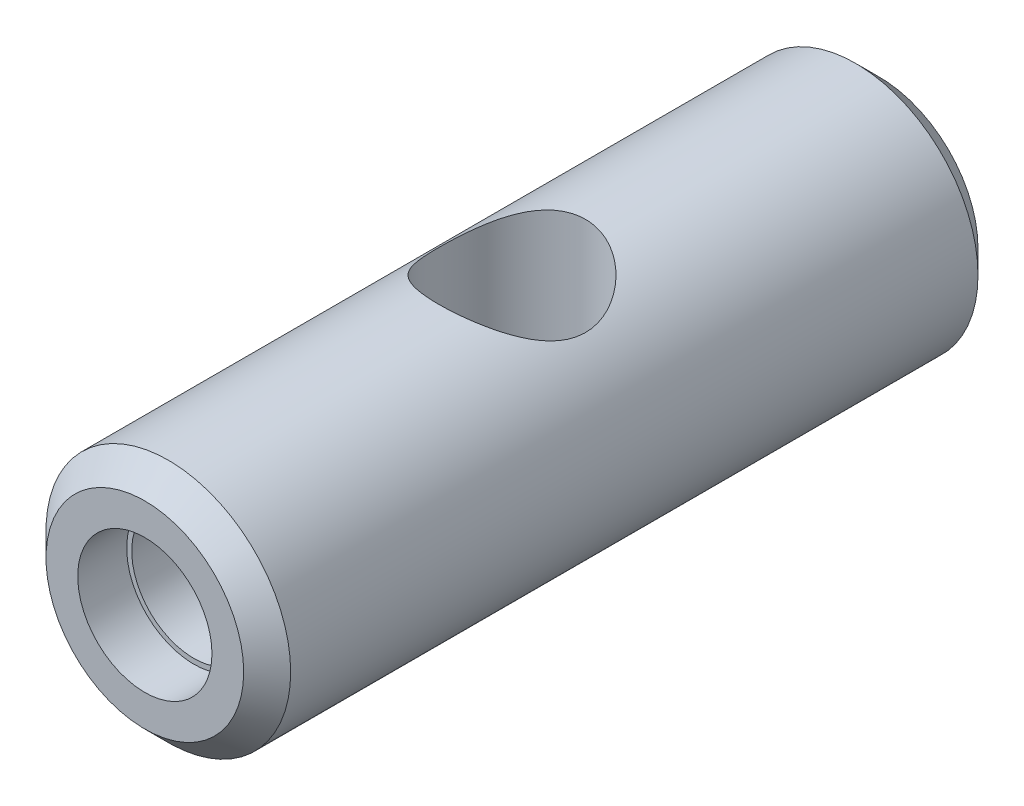
SolidWorks part; units mm, degrees
material "AISI 1020"
ref_plane "Front Plane" through (0, 0, 0) normal (0, 0, 1) x (1, 0, 0)
ref_plane "Top Plane" through (0, 0, 0) normal (0, 1, 0) x (1, 0, 0)
ref_plane "Right Plane" through (0, 0, 0) normal (1, 0, 0) x (0, 0, -1)
sketch "Sketch1" plane through (0, 0, 0) normal (0, 0, 1) x (1, 0, 0)
  circle A0 centre (0, 0) radius 7.9343
  dimension "D1" = 15.8687
extrude "Boss-Extrude1" add sketch "Sketch1" against normal blind 47.625
sketch "Sketch3" plane through (0, 0, 0) normal (0, 1, 0) x (1, 0, 0)
  line L0 (-7.9343, 23.8125) -> (7.9343, 23.8125) construction
  line L1 (-7.9343, 47.625) -> (-7.9343, 0) construction
  line L2 (7.9343, 0) -> (7.9343, 47.625) construction
  line L3 (0, 0) -> (0, 47.625) construction
  line L4 (-7.9343, 0) -> (7.9343, 0) construction
  line L5 (7.9343, 47.625) -> (-7.9343, 47.625) construction
  circle A0 centre (0, 23.8125) radius 4.7688
  dimension "D1" = 9.5377
extrude "Cut-Extrude1" cut sketch "Sketch3" against normal mid plane 28.575
sketch "Sketch2" plane through (0, 0, 0) normal (0, 0, 1) x (1, 0, 0)
  circle A0 centre (0, 0) radius 4.0259
  dimension "D1" = 8.0518
extrude "Cut-Extrude2" cut sketch "Sketch2" against normal blind 25.4
sketch "Sketch5" plane through (0, 0, 0) normal (0, 0, 1) x (1, 0, 0)
  circle A0 centre (0, 0) radius 4.3529
  dimension "D1" = 8.7058
extrude "Cut-Extrude3" cut sketch "Sketch5" against normal blind 3.175
chamfer "Chamfer1" distance 1.524 distance2 1.524 2 edges at (7.9343, 0, 0) (7.9343, 0, -47.625)
